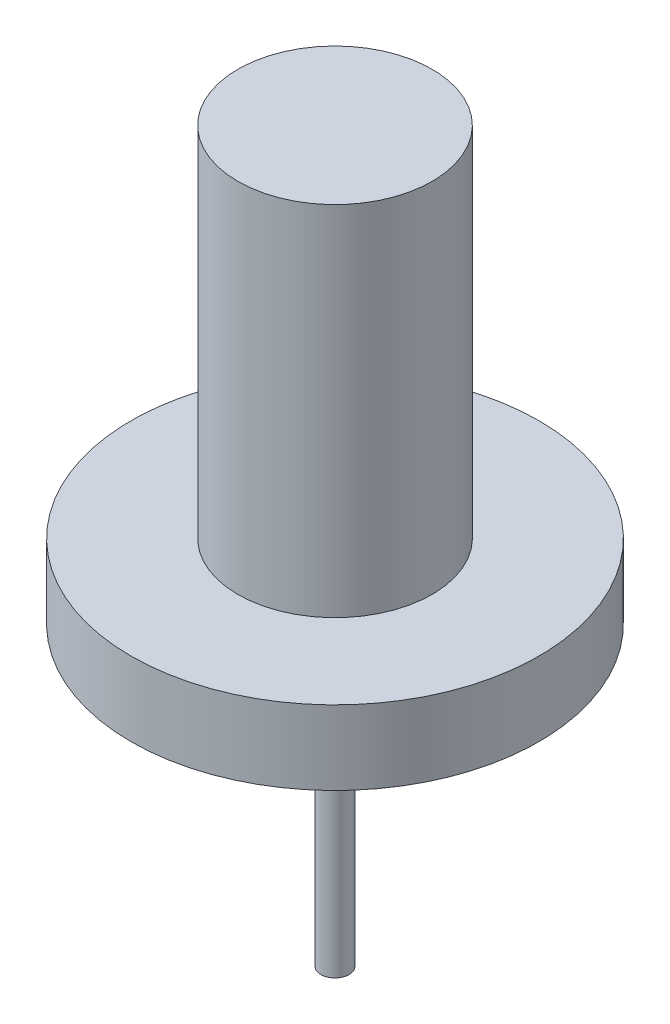
SolidWorks part; units mm, degrees
ref_plane "Front Plane" through (0, 0, 0) normal (0, 0, 1) x (1, 0, 0)
ref_plane "Top Plane" through (0, 0, 0) normal (0, 1, 0) x (1, 0, 0)
ref_plane "Right Plane" through (0, 0, 0) normal (1, 0, 0) x (0, 0, -1)
sketch "Sketch1" plane through (0, 0, 0) normal (0, 1, 0) x (1, 0, 0)
  circle A0 centre (0, 0) radius 34.925
  dimension "D1" = 69.85
extrude "Extrude1" add sketch "Sketch1" along normal blind 12.7
sketch "Sketch2" plane through (0, 12.7, 0) normal (0, 1, 0) x (1, 0, 0)
  circle A0 centre (0, 0) radius 16.637
  dimension "D1" = 33.274
extrude "Extrude2" add sketch "Sketch2" along normal blind 61.2648
sketch "Sketch3" plane through (0, 0, 0) normal (0, -1, 0) x (1, 0, 0)
  circle A0 centre (0, 0) radius 2.4079
extrude "Extrude3" add sketch "Sketch3" along normal blind 50.8
